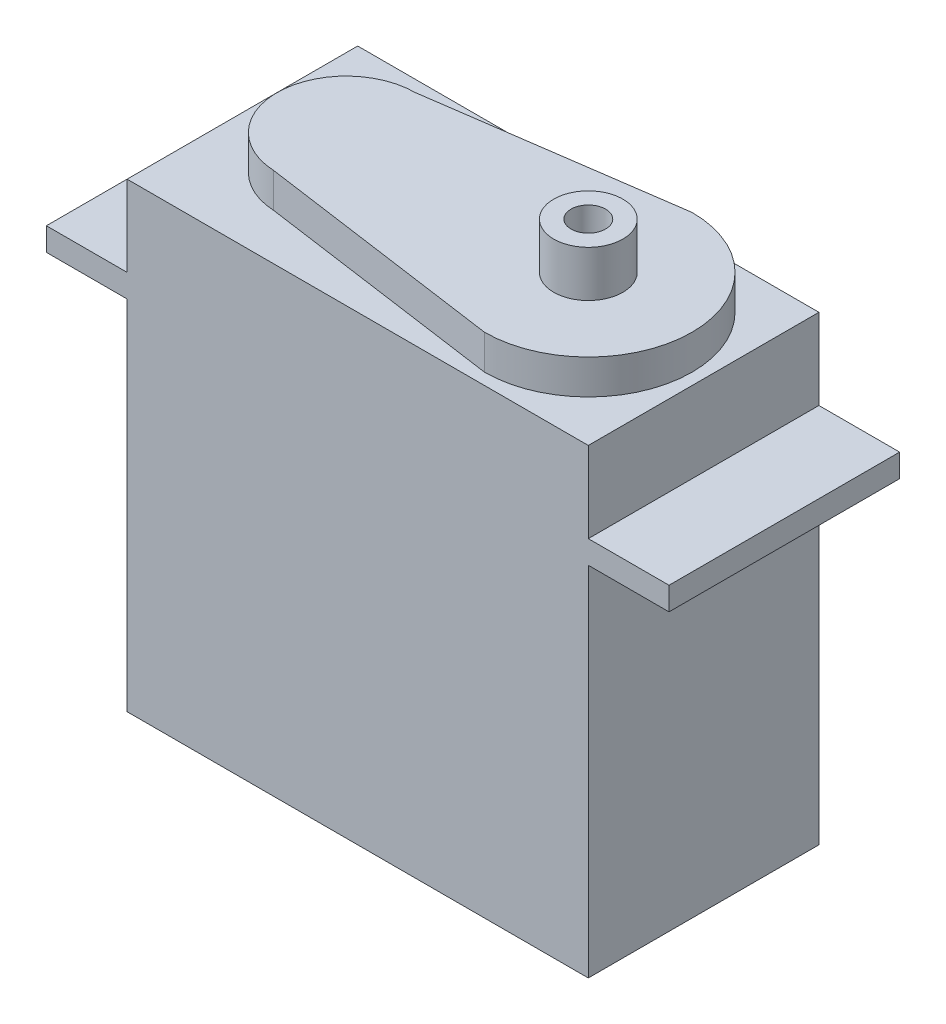
SolidWorks part; units mm, degrees
ref_plane "前视基准面" through (0, 0, 0) normal (0, 0, 1) x (1, 0, 0)
ref_plane "上视基准面" through (0, 0, 0) normal (0, 1, 0) x (1, 0, 0)
ref_plane "右视基准面" through (0, 0, 0) normal (1, 0, 0) x (0, 0, -1)
sketch "草图1" plane through (0, 0, 0) normal (0, 0, 1) x (1, 0, 0)
  line L1 (-20, 20) -> (20, 20)
  line L2 (-20, 20) -> (-20, -20)
  line L3 (-20, -20) -> (20, -20)
  line L4 (20, 20) -> (20, -20)
  line L5 (-20, 20) -> (20, -20) construction
  line L6 (-20, -20) -> (20, 20) construction
  point P0 (0, 0)
  dimension "D1" = 40
  dimension "D2" = 40
extrude "凸台-拉伸1" add sketch "草图1" along normal blind 20
sketch "草图2" plane through (0, 20, 0) normal (0, 1, 0) x (1, 0, 0)
  line L3 (20, -20) -> (20, 0) construction
  line L4 (-20, -20) -> (-20, 0) construction
  line L5 (10, -1) -> (-11, -4)
  line L6 (-11.2901, -15.993) -> (10, -19)
  arc A0 (10, -19) -> (10, -1) centre (10, -10) ccw
  arc A1 (-11, -4) -> (-11.2901, -15.993) centre (-11, -10) ccw
  point P7 (19, -10)
  point P10 (10, -10)
  point P13 (-17, -10)
  point P16 (-11, -10)
  dimension "D2" = 1
  dimension "D3" = 9
  dimension "D4" = 3
  dimension "D5" = 6
extrude "凸台-拉伸2" add sketch "草图2" along normal blind 3 contours L5 A1 L6 A0
sketch "草图5" plane through (0, 23, 0) normal (0, 1, 0) x (1, 0, 0)
  line L0 (-23.0759, -10) -> (28.1102, -10) construction
  line L1 (20, 0) -> (-20, 0) construction
  line L2 (20, -20) -> (20, 0) construction
  circle A0 centre (10, -10) radius 3
  circle A1 centre (10, -10) radius 1.5
  point P4 (10, -10)
  dimension "D1" = 10
  dimension "D2" = 10
extrude "凸台-拉伸3" add sketch "草图5" along normal blind 4
sketch "草图6" plane through (0, 0, 0) normal (0, 0, -1) x (-1, 0, 0)
  line L0 (-20, -20) -> (-20, 20) construction
  line L1 (-20, 13) -> (-27, 13)
  line L2 (-20, 13) -> (-20, 11)
  line L3 (-20, 11) -> (-27, 11)
  line L4 (-27, 13) -> (-27, 11)
  line L5 (-20, 20) -> (20, 20) construction
  line L6 (20, 20) -> (20, -20) construction
  line L7 (20, 13) -> (27, 13)
  line L8 (20, 13) -> (20, 11)
  line L9 (20, 11) -> (27, 11)
  line L10 (27, 13) -> (27, 11)
  dimension "D1" = 7
  dimension "D2" = 7
  dimension "D3" = 2
  dimension "D4" = 7
  dimension "D5" = 2
  dimension "D6" = 7
extrude "凸台-拉伸4" add sketch "草图6" against normal blind 20
sketch "草图7" plane through (0, 27, 0) normal (0, 1, 0) x (1, 0, 0)
  line L0 (-0.7099, -10) -> (20.7099, -10)
  line L1 (10, -0.6903) -> (10, -19.3097)
  point P4 (10, -10)
  point P7 (10, -10)
